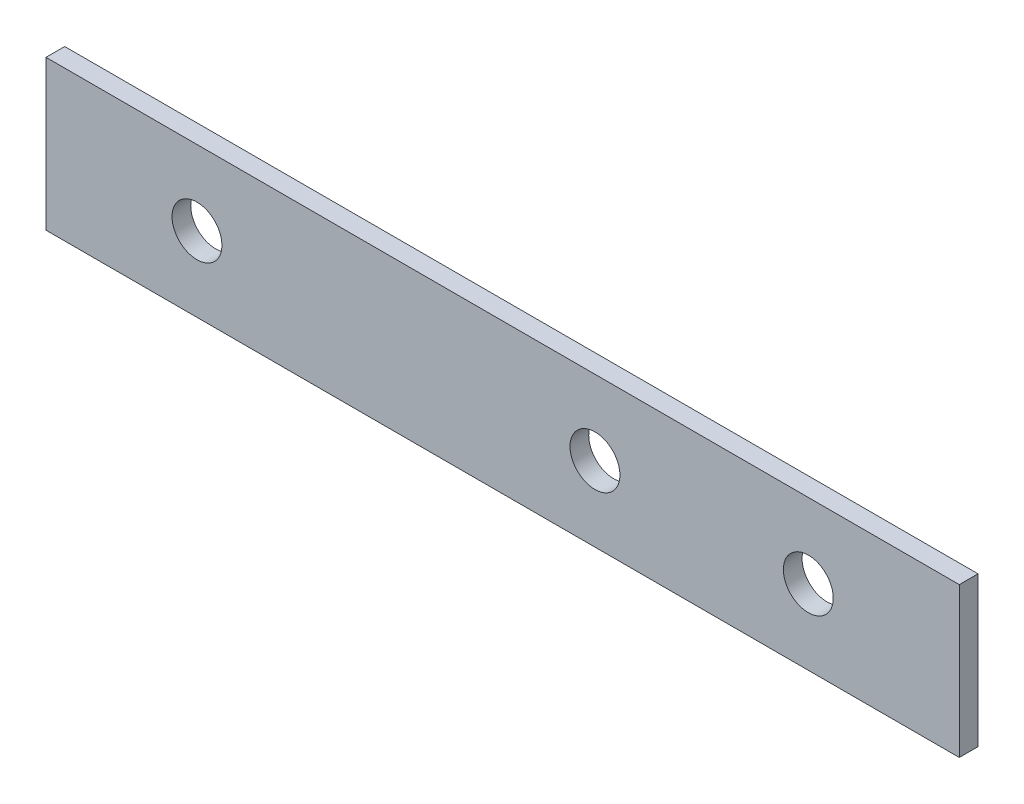
SolidWorks part; units mm, degrees
ref_plane "Front Plane" through (0, 0, 0) normal (0, 0, 1) x (1, 0, 0)
ref_plane "Top Plane" through (0, 0, 0) normal (0, 1, 0) x (1, 0, 0)
ref_plane "Right Plane" through (0, 0, 0) normal (1, 0, 0) x (0, 0, -1)
sketch "Sketch1" plane through (0, 0, 0) normal (0, 0, 1) x (1, 0, 0)
  line L1 (0, 0) -> (232.41, 0)
  line L2 (0, 0) -> (0, 38.1)
  line L3 (0, 38.1) -> (232.41, 38.1)
  line L4 (232.41, 0) -> (232.41, 38.1)
  circle A0 centre (38.4175, 19.05) radius 6.35
  circle A1 centre (193.9925, 19.05) radius 6.35
  circle A2 centre (139.7, 19.05) radius 6.35
  point P9 (0, 19.05)
  point P10 (160.7813, 19.05)
  dimension "D3" = 12.7
  dimension "D1" = 232.41
  dimension "D2" = 38.1
  dimension "D4" = 155.575
  dimension "D5" = 38.4175
  dimension "D6" = 139.7
  dimension "D7" = 193.9925
extrude "Boss-Extrude1" add sketch "Sketch1" along normal blind 4.7625
